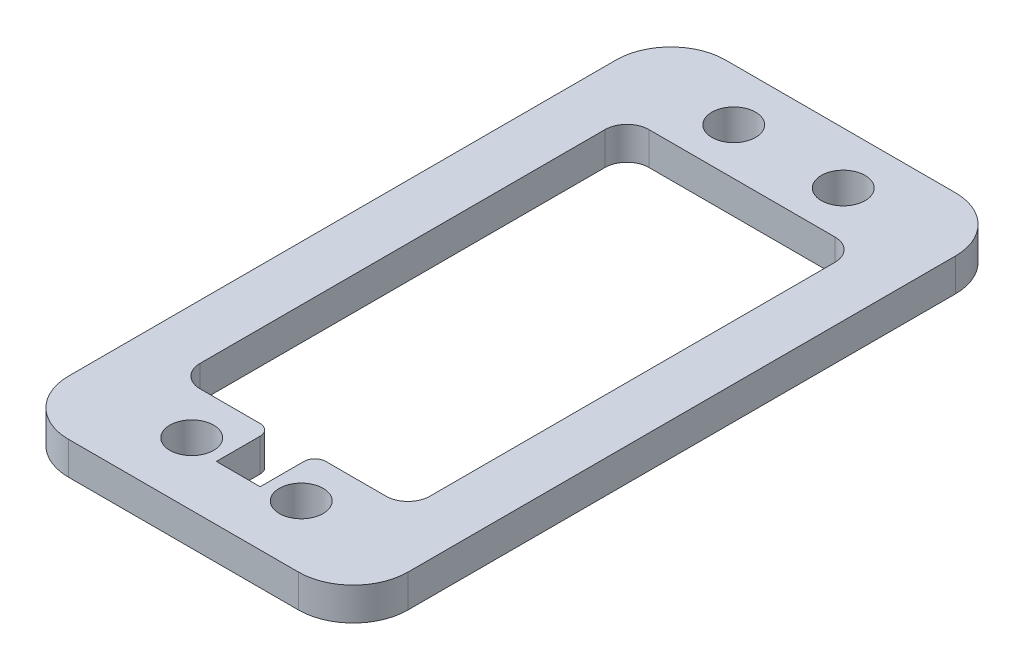
SolidWorks part; units mm, degrees
ref_plane "Front Plane" through (0, 0, 0) normal (0, 0, 1) x (1, 0, 0)
ref_plane "Top Plane" through (0, 0, 0) normal (0, 1, 0) x (1, 0, 0)
ref_plane "Right Plane" through (0, 0, 0) normal (1, 0, 0) x (0, 0, -1)
sketch "Sketch1" plane through (0, 0, 0) normal (0, 1, 0) x (1, 0, 0)
  line L0 (3, -10.6) -> (8.5, -10.6)
  line L1 (-10.5, 39.4) -> (10.5, 39.4)
  line L2 (-15.5, 34.4) -> (-15.5, -15.6)
  line L3 (-10.5, -20.6) -> (10.5, -20.6)
  line L4 (15.5, 34.4) -> (15.5, -15.6)
  line L5 (-8.5, 30.4) -> (8.5, 30.4)
  line L6 (-10.5, 28.4) -> (-10.5, -8.6)
  line L7 (-8.5, -10.6) -> (-3, -10.6)
  line L8 (10.5, 28.4) -> (10.5, -8.6)
  line L10 (-2, -11.6) -> (-2, -15.6)
  line L11 (-2, -15.6) -> (2, -15.6)
  line L12 (2, -11.6) -> (2, -15.6)
  arc A1 (-10.5, -8.6) -> (-8.5, -10.6) centre (-8.5, -8.6) ccw
  arc A2 (8.5, -10.6) -> (10.5, -8.6) centre (8.5, -8.6) ccw
  arc A3 (10.5, 28.4) -> (8.5, 30.4) centre (8.5, 28.4) ccw
  arc A4 (-10.5, 28.4) -> (-8.5, 30.4) centre (-8.5, 28.4) cw
  arc A5 (15.5, -15.6) -> (10.5, -20.6) centre (10.5, -15.6) cw
  arc A6 (-15.5, -15.6) -> (-10.5, -20.6) centre (-10.5, -15.6) ccw
  arc A7 (15.5, 34.4) -> (10.5, 39.4) centre (10.5, 34.4) ccw
  arc A8 (-15.5, 34.4) -> (-10.5, 39.4) centre (-10.5, 34.4) cw
  arc A9 (3, -10.6) -> (2, -11.6) centre (3, -11.6) ccw
  arc A10 (-3, -10.6) -> (-2, -11.6) centre (-3, -11.6) cw
  circle A11 centre (-5, 34.65) radius 2
  circle A12 centre (5, 34.65) radius 2
  circle A13 centre (-5, -14.85) radius 2
  circle A14 centre (5, -14.85) radius 2
  point P10 (-10.5, -10.6)
  point P14 (10.5, -10.6)
  point P19 (-10.5, 30.4)
  point P24 (-15.5, -20.6)
  point P29 (-15.5, 39.4)
  point P36 (2, -10.6)
  dimension "D1" = 41
  dimension "D9" = 2
  dimension "D10" = 5
  dimension "D14" = 1
  dimension "D15" = 5
  dimension "D17" = 4
  dimension "D18" = 4
  dimension "D20" = 4
  dimension "D21" = 4
  dimension "D2" = 10.6
  dimension "D3" = 60
  dimension "D4" = 10
  dimension "D5" = 21
  dimension "D6" = 10.5
  dimension "D7" = 5
  dimension "D8" = 5
  dimension "D11" = 4
  dimension "D12" = 2
  dimension "D13" = 5
  dimension "D16" = 5
  dimension "D19" = 14.85
  dimension "D22" = 34.65
extrude "Boss-Extrude1" add sketch "Sketch1" along normal blind 3 contours A8 L2 A6 L3 A5 L4 A7 L1 A14 A13 A12 A11 A10 L7 A1 L6 A4 L5 A3 L8 A2 L0 A9 L12 L11 L10
